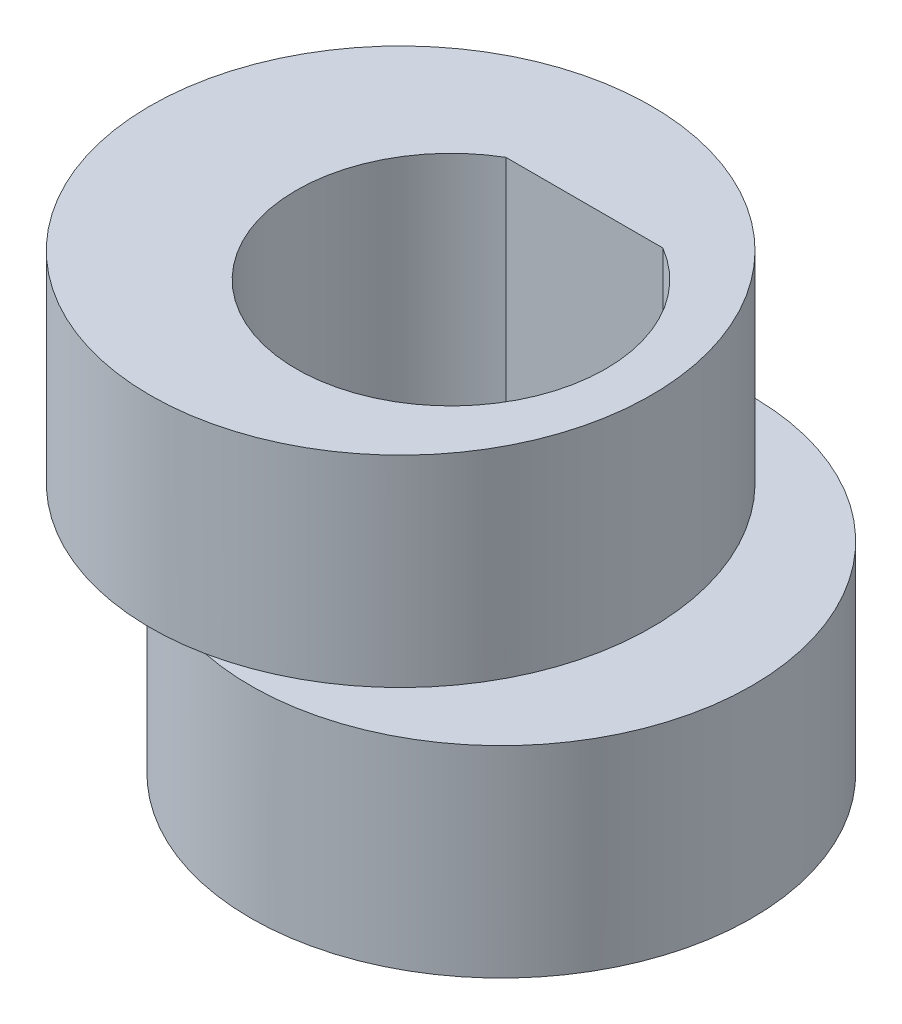
SolidWorks part; units mm, degrees
ref_plane "Alzado" through (0, 0, 0) normal (0, 0, 1) x (1, 0, 0)
ref_plane "Planta" through (0, 0, 0) normal (0, 1, 0) x (1, 0, 0)
ref_plane "Vista lateral" through (0, 0, 0) normal (1, 0, 0) x (0, 0, -1)
sketch "Croquis1" plane through (0, 0, 0) normal (0, 1, 0) x (1, 0, 0)
  circle A0 centre (1, 0) radius 4.98
  dimension "D1" = 9.96
  dimension "D2" = 1
extrude "Saliente-Extruir1" add sketch "Croquis1" along normal blind 4
sketch "Croquis2" plane through (0, 4, 0) normal (0, 1, 0) x (1, 0, 0)
  circle A0 centre (-1, 0) radius 4.98
  dimension "D1" = 9.96
  dimension "D2" = 1
extrude "Saliente-Extruir2" add sketch "Croquis2" along normal blind 4
sketch "Croquis3" plane through (0, 0, 0) normal (0, 1, 0) x (1, 0, 0)
  line L0 (-1.5598, 2.65) -> (1.5598, 2.65)
  arc A0 (-1.5598, 2.65) -> (1.5598, 2.65) centre (0, 0) ccw
  dimension "D1" = 6.15
  dimension "D2" = 2.65
extrude "Cortar-Extruir1" cut sketch "Croquis3" along normal through all
